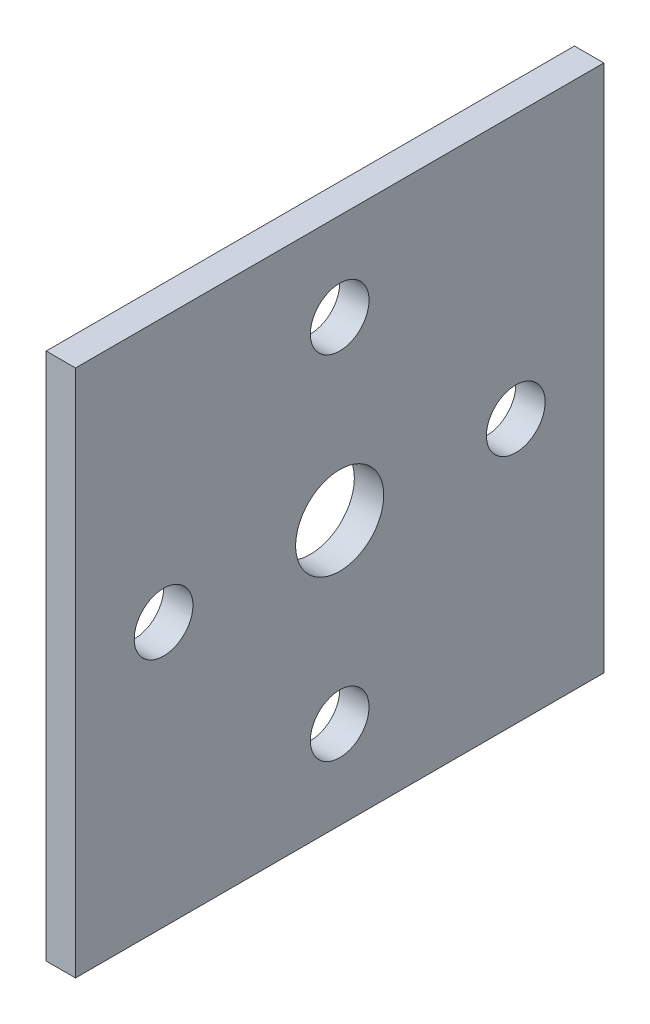
SolidWorks part; units mm, degrees
material "1023 Carbon Steel Sheet (SS)"
ref_plane "Front Plane" through (0, 0, 0) normal (0, 0, 1) x (1, 0, 0)
ref_plane "Top Plane" through (0, 0, 0) normal (0, 1, 0) x (1, 0, 0)
ref_plane "Right Plane" through (0, 0, 0) normal (1, 0, 0) x (0, 0, -1)
sketch "Sketch1" plane through (0, 0, 0) normal (1, 0, 0) x (0, 0, -1)
  line L1 (-28.575, -28.575) -> (28.575, -28.575)
  line L2 (-28.575, -28.575) -> (-28.575, 28.575)
  line L3 (-28.575, 28.575) -> (28.575, 28.575)
  line L4 (28.575, -28.575) -> (28.575, 28.575)
  line L5 (-28.575, -28.575) -> (28.575, 28.575) construction
  line L6 (-28.575, 28.575) -> (28.575, -28.575) construction
  circle A1 centre (0, 0) radius 4.7625
  circle A2 centre (0, 0) radius 11.1125 construction
  dimension "D1" = 9.525
  dimension "D2" = 22.225
  dimension "D3" = 57.15
  dimension "D4" = 57.15
extrude "Boss-Extrude1" add sketch "Sketch1" along normal blind 3.175
sketch "Sketch2" plane through (0, 0, 0) normal (1, 0, 0) x (0, 0, -1)
  line L0 (-28.575, 0) -> (28.575, 0) construction
  line L1 (28.575, -28.575) -> (28.575, 28.575) construction
  circle A0 centre (0, 19.05) radius 3.175
  point P7 (0, 0)
  point P12 (0, 0)
  dimension "D2" = 6.35
  dimension "D1" = 19.05
extrude "Cut-Extrude1" cut sketch "Sketch2" along normal through all
pattern_circular "CirPattern1" count 4 over 360 about axis through (0, 0, 0) along (1, 0, 0) of "Cut-Extrude1"
